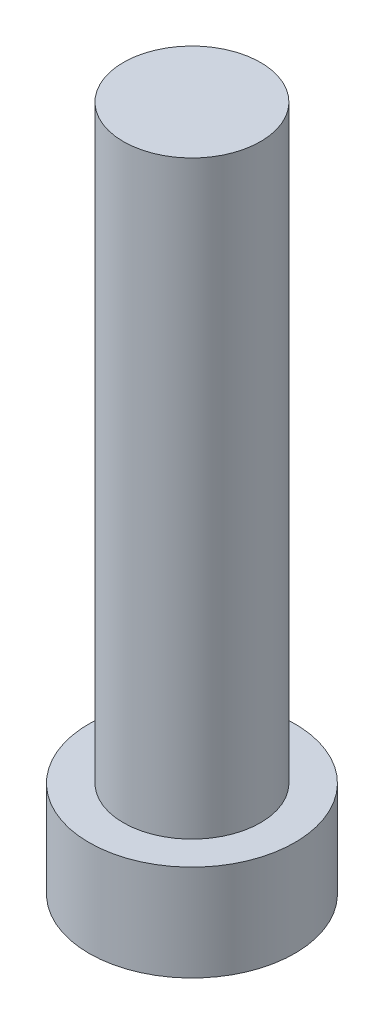
SolidWorks part; units mm, degrees
ref_plane "Front Plane" through (0, 0, 0) normal (0, 0, 1) x (1, 0, 0)
ref_plane "Top Plane" through (0, 0, 0) normal (0, 1, 0) x (1, 0, 0)
ref_plane "Right Plane" through (0, 0, 0) normal (1, 0, 0) x (0, 0, -1)
sketch "Sketch1" plane through (0, 0, 0) normal (0, 1, 0) x (1, 0, 0)
  circle A0 centre (0, 0) radius 7.5
  dimension "D1" = 15
extrude "Boss-Extrude1" add sketch "Sketch1" along normal blind 7
sketch "Sketch2" plane through (0, 7, 0) normal (0, 1, 0) x (1, 0, 0)
  circle A0 centre (0, 0) radius 5
  circle A1 centre (0, 0) radius 7.5
  circle A2 centre (0, 0) radius 7.5
  dimension "D2" = 10
  dimension "D1" = 0
extrude "Boss-Extrude2" add sketch "Sketch2" along normal blind 43 contours A0
